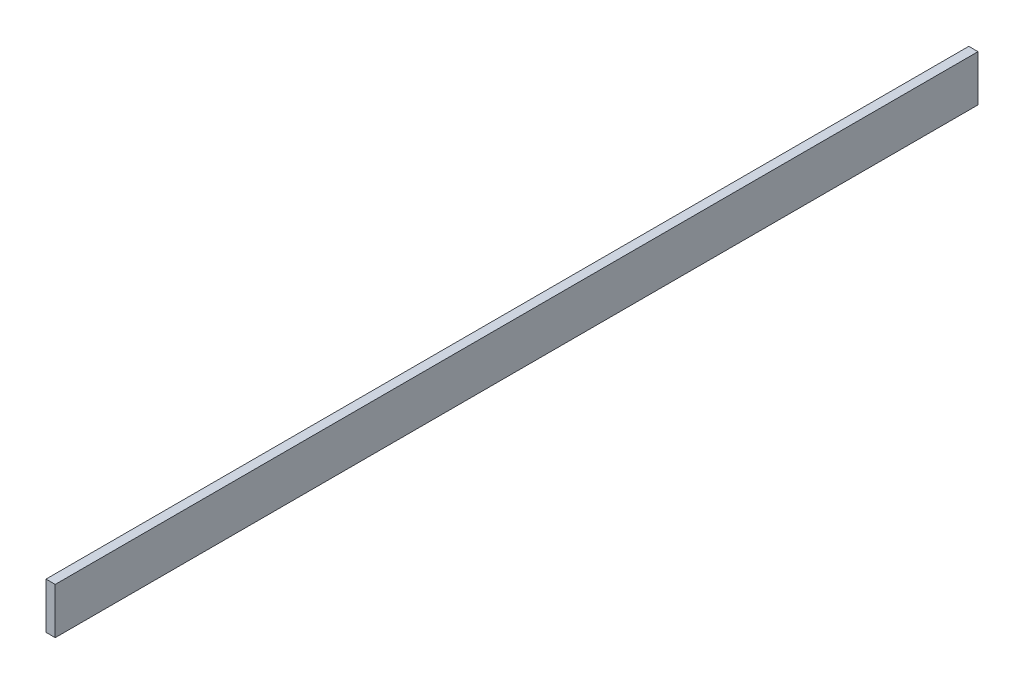
SolidWorks part; units mm, degrees
ref_plane "Front Plane" through (0, 0, 0) normal (0, 0, 1) x (1, 0, 0)
ref_plane "Top Plane" through (0, 0, 0) normal (0, 1, 0) x (1, 0, 0)
ref_plane "Right Plane" through (0, 0, 0) normal (1, 0, 0) x (0, 0, -1)
sketch "Sketch1" plane through (0, 0, 0) normal (0, 0, 1) x (1, 0, 0)
  line L1 (-10, 50) -> (10, 50)
  line L2 (-10, 50) -> (-10, -50)
  line L3 (-10, -50) -> (10, -50)
  line L4 (10, 50) -> (10, -50)
  line L5 (-10, 50) -> (10, -50) construction
  line L6 (-10, -50) -> (10, 50) construction
  point P0 (0, 0)
extrude "Boss-Extrude1" add sketch "Sketch1" along normal blind 2000
